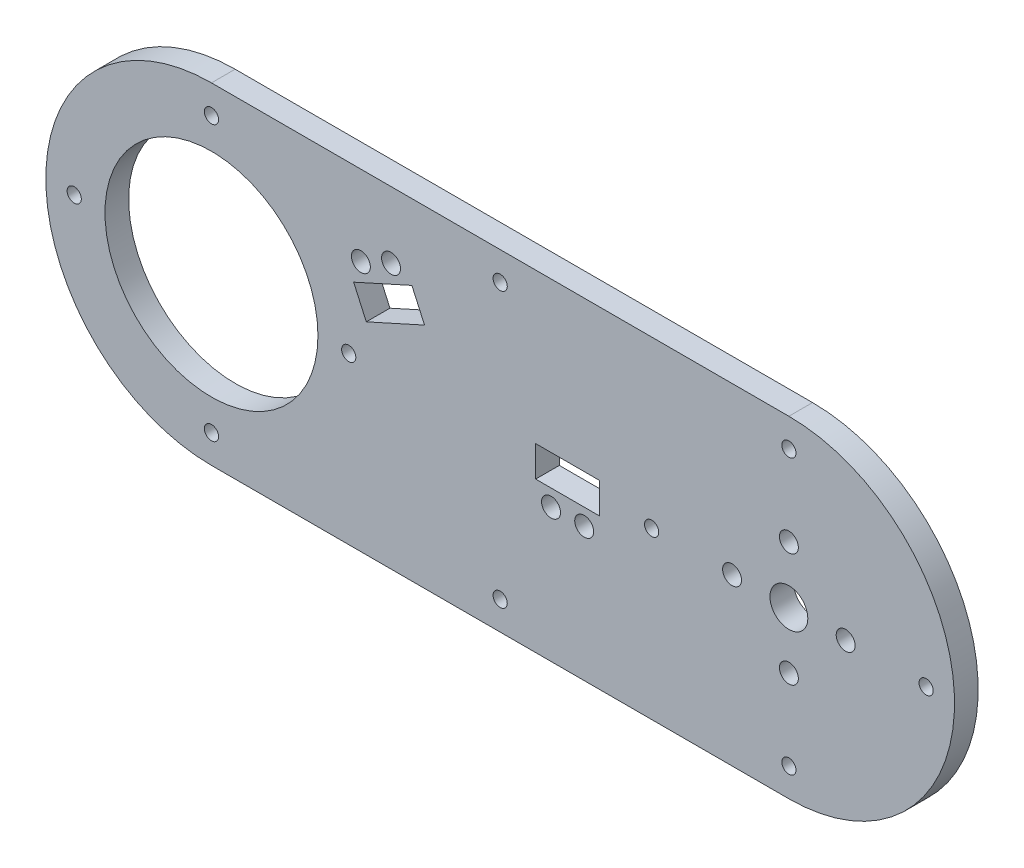
SolidWorks part; units mm, degrees
ref_plane "Front Plane" through (0, 0, 0) normal (0, 0, 1) x (1, 0, 0)
ref_plane "Top Plane" through (0, 0, 0) normal (0, 1, 0) x (1, 0, 0)
ref_plane "Right Plane" through (0, 0, 0) normal (1, 0, 0) x (0, 0, -1)
sketch "Sketch1" plane through (0, 0, 0) normal (0, 0, 1) x (1, 0, 0)
  line L0 (61, 0) -> (-61, 0) construction
  line L2 (61, -35) -> (-61, -35)
  line L3 (61, 35) -> (-61, 35)
  line L17 (7.5, 3.25) -> (7.5, -3.25)
  line L20 (7.5, -3.25) -> (21, -3.25)
  line L23 (21, -3.25) -> (21, 3.25)
  line L24 (21, 3.25) -> (7.5, 3.25)
  line L37 (-61, 0) -> (-30.9578, 13.5583) construction
  line L38 (-30.9578, 13.5583) -> (-28.284, 7.6337)
  line L39 (-28.284, 7.6337) -> (-15.9791, 13.187)
  line L40 (-15.9791, 13.187) -> (-18.6529, 19.1116)
  line L41 (-18.6529, 19.1116) -> (-30.9578, 13.5583)
  arc A0 (61, -35) -> (61, 35) centre (61, 0) ccw
  arc A1 (-61, 35) -> (-61, -35) centre (-61, 0) ccw
  circle A2 centre (61, 0) radius 4
  circle A3 centre (-61, 0) radius 22.5
  circle A4 centre (-61, -29) radius 1.5
  circle A5 centre (-61, 29) radius 1.5
  circle A6 centre (61, 29) radius 1.5
  circle A7 centre (61, -29) radius 1.5
  circle A9 centre (0, 29) radius 1.5
  circle A12 centre (-90, 0) radius 1.5
  circle A13 centre (-32, 0) radius 1.5
  circle A16 centre (90, 0) radius 1.5
  circle A17 centre (32, 0) radius 1.5
  circle A34 centre (61, 12) radius 2
  circle A35 centre (61, -12) radius 2
  circle A36 centre (49, 0) radius 2
  circle A37 centre (73, 0) radius 2
  circle A44 centre (10.75, -6.75) radius 2
  circle A45 centre (17.75, -6.75) radius 2
  circle A46 centre (-23.0549, 20.9648) radius 2
  circle A47 centre (-29.4352, 18.0853) radius 2
  circle A48 centre (0, -29) radius 1.5
  point P5 (0, 0)
  point P27 (-61, 0)
  point P28 (7.5, 0)
  point P32 (-61, 0)
  point P74 (14.25, -6.75)
  point P83 (-26.2451, 19.5251)
  dimension "D1" = 8
  dimension "D3" = 6
  dimension "D4" = 3
  dimension "D5" = 6
  dimension "D6" = 3
  dimension "D8" = 3
  dimension "D9" = 3
  dimension "D12" = 3
  dimension "D13" = 6
  dimension "D14" = 70
  dimension "D15" = 12
  dimension "D16" = 12
  dimension "D19" = 3
  dimension "D20" = 3
  dimension "D24" = 29
  dimension "D25" = 3
  dimension "D26" = 3
  dimension "D27" = 4
  dimension "D28" = 4
  dimension "D29" = 4
  dimension "D30" = 29
  dimension "D31" = 13.5
  dimension "D32" = 6.5
  dimension "D33" = 68.5
  dimension "D34" = 3
  dimension "D45" = 45
  dimension "D22" = 4
  dimension "D41" = 4
  dimension "D42" = 4
  dimension "D7" = 122
  dimension "D10" = 6
  dimension "D11" = 6
  dimension "D17" = 12
  dimension "D18" = 58
  dimension "D21" = 12
  dimension "D23" = 29
  dimension "D35" = 6
  dimension "D43" = 7
  dimension "D44" = 32.96
extrude "Boss-Extrude1" add sketch "Sketch1" along normal blind 5
